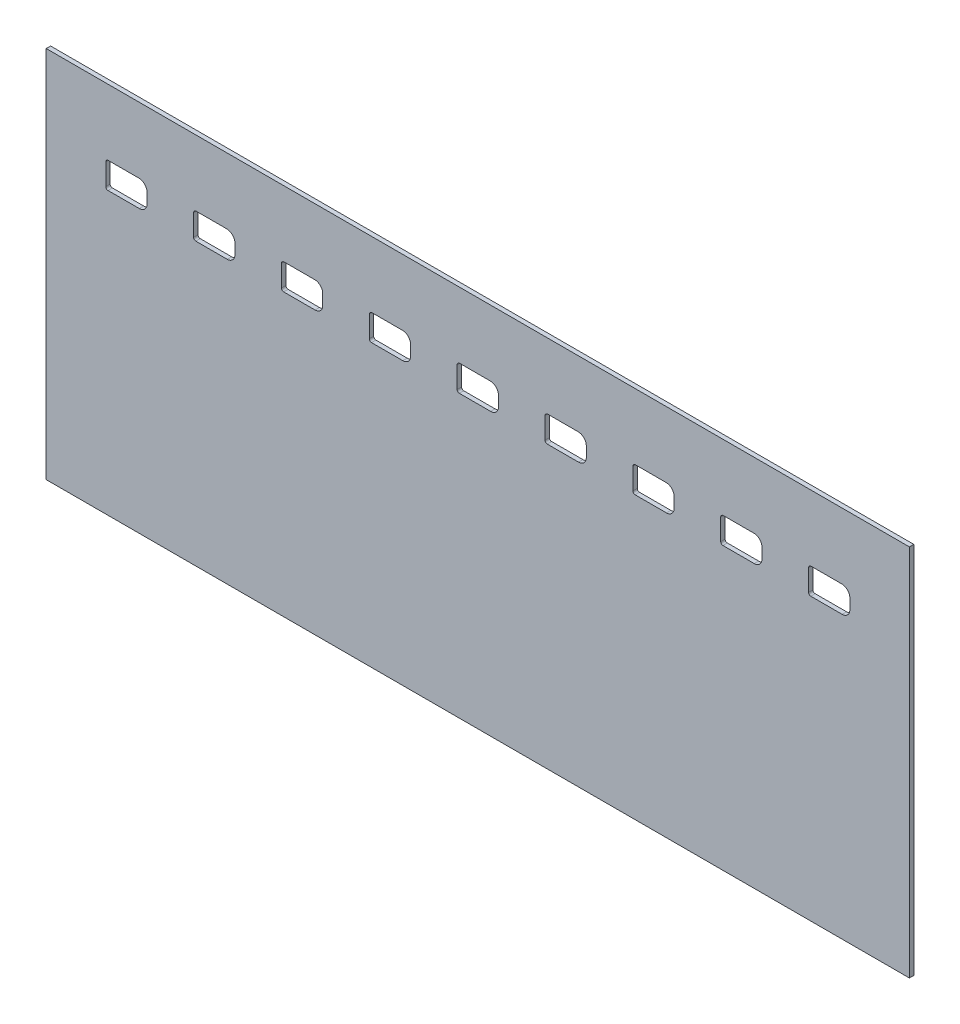
SolidWorks part; units mm, degrees
ref_plane "Front Plane" through (0, 0, 0) normal (0, 0, 1) x (1, 0, 0)
ref_plane "Top Plane" through (0, 0, 0) normal (0, 1, 0) x (1, 0, 0)
ref_plane "Right Plane" through (0, 0, 0) normal (1, 0, 0) x (0, 0, -1)
sketch "Model" plane through (0, 0, 0) normal (0, 0, 1) x (1, 0, 0)
  line L1 (196.5, -85) -> (-196.5, -85)
  line L2 (196.5, -85) -> (196.5, 85)
  line L3 (196.5, 85) -> (-196.5, 85)
  line L4 (-196.5, -85) -> (-196.5, 85)
  line L5 (196.5, -85) -> (-196.5, 85) construction
  line L6 (196.5, 85) -> (-196.5, -85) construction
  point P0 (0, 0)
  dimension "D1" = 170
  dimension "D2" = 393
extrude "Boss-Extrude1" add sketch "Model" along normal blind 2
sketch "Sketch1" plane through (0, 0, 2) normal (0, 0, 1) x (1, 0, 0)
  line L0 (-154.125, 43.1) -> (-168.4, 43.1)
  line L1 (-168.2, 55) -> (-154.325, 55)
  line L2 (-169.4, 44.1) -> (-169.4, 53.8)
  line L3 (-150.6, 46.625) -> (-150.6, 51.275)
  line L4 (-114.125, 43.1) -> (-128.4, 43.1)
  line L5 (-169.4, 48.95) -> (-196.5, 48.95) construction
  line L6 (-128.2, 55) -> (-114.325, 55)
  line L7 (-129.4, 44.1) -> (-129.4, 53.8)
  line L8 (-110.6, 46.625) -> (-110.6, 51.275)
  line L9 (-74.125, 43.1) -> (-88.4, 43.1)
  line L10 (-88.2, 55) -> (-74.325, 55)
  line L11 (-89.4, 44.1) -> (-89.4, 53.8)
  line L12 (-70.6, 46.625) -> (-70.6, 51.275)
  line L13 (-34.125, 43.1) -> (-48.4, 43.1)
  line L14 (-48.2, 55) -> (-34.325, 55)
  line L15 (-49.4, 44.1) -> (-49.4, 53.8)
  line L16 (-30.6, 46.625) -> (-30.6, 51.275)
  line L17 (5.875, 43.1) -> (-8.4, 43.1)
  line L18 (-8.2, 55) -> (5.675, 55)
  line L19 (-9.4, 44.1) -> (-9.4, 53.8)
  line L20 (9.4, 46.625) -> (9.4, 51.275)
  line L21 (45.875, 43.1) -> (31.6, 43.1)
  line L22 (31.8, 55) -> (45.675, 55)
  line L23 (30.6, 44.1) -> (30.6, 53.8)
  line L24 (49.4, 46.625) -> (49.4, 51.275)
  line L25 (85.875, 43.1) -> (71.6, 43.1)
  line L26 (71.8, 55) -> (85.675, 55)
  line L27 (70.6, 44.1) -> (70.6, 53.8)
  line L28 (89.4, 46.625) -> (89.4, 51.275)
  line L29 (125.875, 43.1) -> (111.6, 43.1)
  line L30 (111.8, 55) -> (125.675, 55)
  line L31 (110.6, 44.1) -> (110.6, 53.8)
  line L32 (129.4, 46.625) -> (129.4, 51.275)
  line L33 (165.875, 43.1) -> (151.6, 43.1)
  line L34 (151.8, 55) -> (165.675, 55)
  line L35 (150.6, 44.1) -> (150.6, 53.8)
  line L36 (169.4, 46.625) -> (169.4, 51.275)
  line L37 (-161.2625, 55) -> (-161.2625, 75) construction
  line L38 (-196.5, 85) -> (-196.5, -85) construction
  line L39 (169.4, 48.95) -> (196.5, 48.95) construction
  line L40 (196.5, -85) -> (196.5, 85) construction
  arc A0 (-150.6, 46.625) -> (-154.125, 43.1) centre (-154.125, 46.625) cw
  arc A1 (-150.6, 51.275) -> (-154.325, 55) centre (-154.325, 51.275) ccw
  arc A2 (-168.4, 43.1) -> (-169.4, 44.1) centre (-168.4, 44.1) cw
  arc A3 (-169.4, 53.8) -> (-168.2, 55) centre (-168.2, 53.8) cw
  arc A4 (-110.6, 46.625) -> (-114.125, 43.1) centre (-114.125, 46.625) cw
  arc A5 (-110.6, 51.275) -> (-114.325, 55) centre (-114.325, 51.275) ccw
  arc A6 (-128.4, 43.1) -> (-129.4, 44.1) centre (-128.4, 44.1) cw
  arc A7 (-129.4, 53.8) -> (-128.2, 55) centre (-128.2, 53.8) cw
  arc A8 (-70.6, 46.625) -> (-74.125, 43.1) centre (-74.125, 46.625) cw
  arc A9 (-70.6, 51.275) -> (-74.325, 55) centre (-74.325, 51.275) ccw
  arc A10 (-88.4, 43.1) -> (-89.4, 44.1) centre (-88.4, 44.1) cw
  arc A11 (-89.4, 53.8) -> (-88.2, 55) centre (-88.2, 53.8) cw
  arc A12 (-30.6, 46.625) -> (-34.125, 43.1) centre (-34.125, 46.625) cw
  arc A13 (-30.6, 51.275) -> (-34.325, 55) centre (-34.325, 51.275) ccw
  arc A14 (-48.4, 43.1) -> (-49.4, 44.1) centre (-48.4, 44.1) cw
  arc A15 (-49.4, 53.8) -> (-48.2, 55) centre (-48.2, 53.8) cw
  arc A16 (9.4, 46.625) -> (5.875, 43.1) centre (5.875, 46.625) cw
  arc A17 (9.4, 51.275) -> (5.675, 55) centre (5.675, 51.275) ccw
  arc A18 (-8.4, 43.1) -> (-9.4, 44.1) centre (-8.4, 44.1) cw
  arc A19 (-9.4, 53.8) -> (-8.2, 55) centre (-8.2, 53.8) cw
  arc A20 (49.4, 46.625) -> (45.875, 43.1) centre (45.875, 46.625) cw
  arc A21 (49.4, 51.275) -> (45.675, 55) centre (45.675, 51.275) ccw
  arc A22 (31.6, 43.1) -> (30.6, 44.1) centre (31.6, 44.1) cw
  arc A23 (30.6, 53.8) -> (31.8, 55) centre (31.8, 53.8) cw
  arc A24 (89.4, 46.625) -> (85.875, 43.1) centre (85.875, 46.625) cw
  arc A25 (89.4, 51.275) -> (85.675, 55) centre (85.675, 51.275) ccw
  arc A26 (71.6, 43.1) -> (70.6, 44.1) centre (71.6, 44.1) cw
  arc A27 (70.6, 53.8) -> (71.8, 55) centre (71.8, 53.8) cw
  arc A28 (129.4, 46.625) -> (125.875, 43.1) centre (125.875, 46.625) cw
  arc A29 (129.4, 51.275) -> (125.675, 55) centre (125.675, 51.275) ccw
  arc A30 (111.6, 43.1) -> (110.6, 44.1) centre (111.6, 44.1) cw
  arc A31 (110.6, 53.8) -> (111.8, 55) centre (111.8, 53.8) cw
  arc A32 (169.4, 46.625) -> (165.875, 43.1) centre (165.875, 46.625) cw
  arc A33 (169.4, 51.275) -> (165.675, 55) centre (165.675, 51.275) ccw
  arc A34 (151.6, 43.1) -> (150.6, 44.1) centre (151.6, 44.1) cw
  arc A35 (150.6, 53.8) -> (151.8, 55) centre (151.8, 53.8) cw
  dimension "D1" = 20
extrude "Cut-Extrude1" cut sketch "Sketch1" against normal through all
